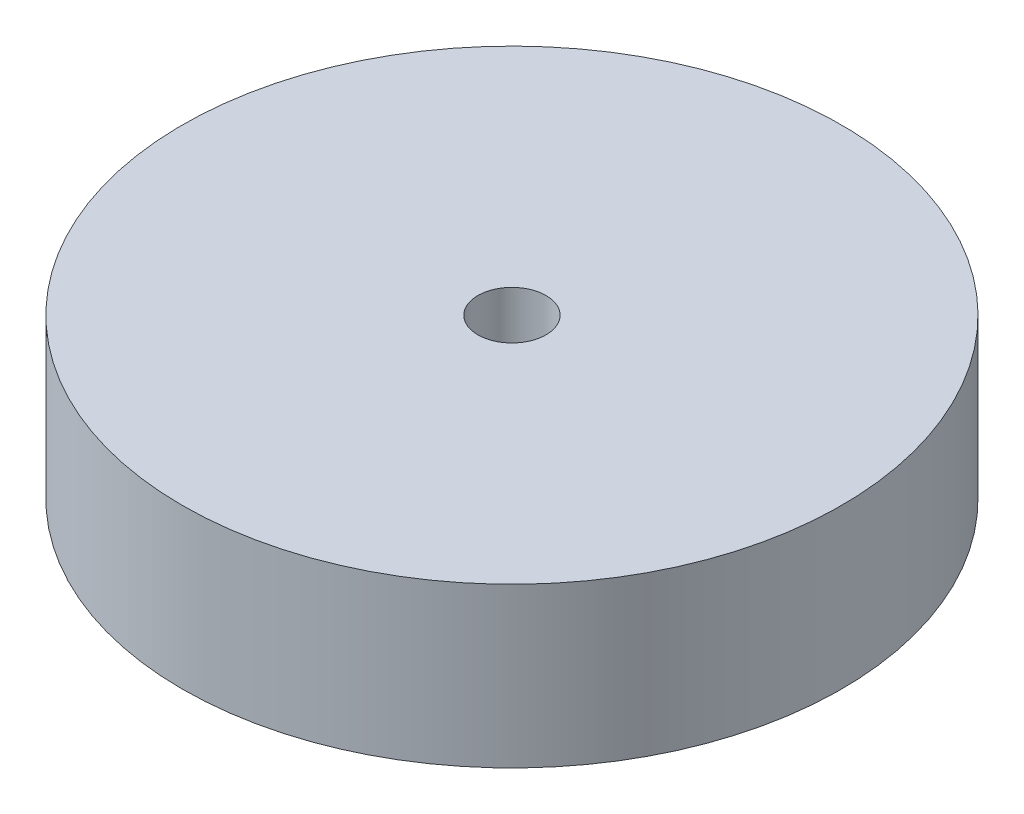
SolidWorks part; units mm, degrees
ref_plane "前视" through (0, 0, 0) normal (0, 0, 1) x (1, 0, 0)
ref_plane "上视" through (0, 0, 0) normal (0, 1, 0) x (1, 0, 0)
ref_plane "右视" through (0, 0, 0) normal (1, 0, 0) x (0, 0, -1)
sketch "Sketch1" plane through (0, 0, 0) normal (0, 1, 0) x (1, 0, 0)
  circle A0 centre (0, 0) radius 29
  circle A1 centre (0, 0) radius 3
extrude "Extrude1" add sketch "Sketch1" along normal blind 14
